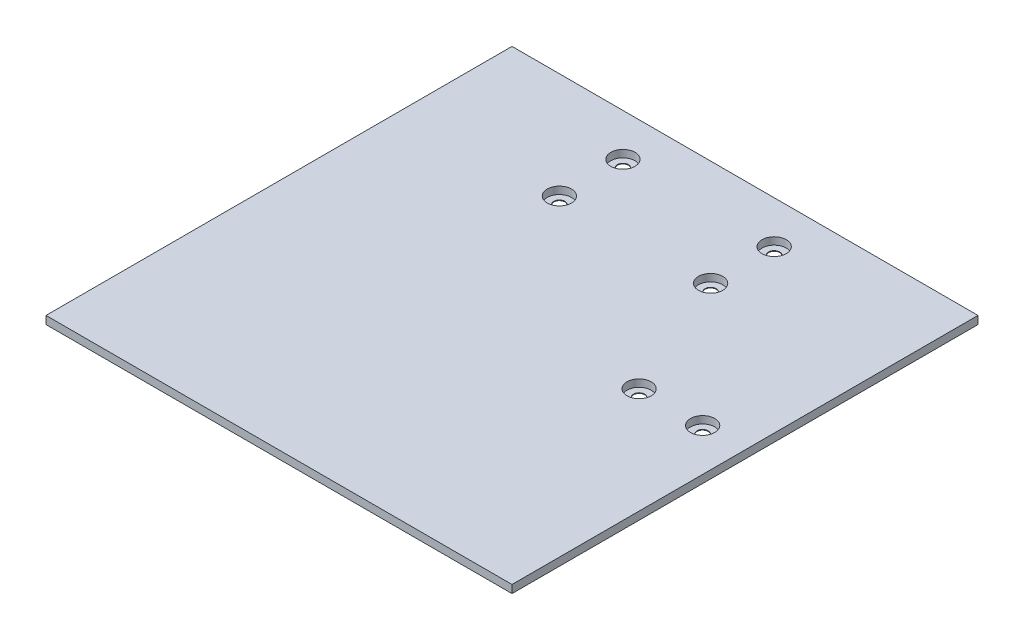
SolidWorks part; units mm, degrees
ref_plane "Front Plane" through (0, 0, 0) normal (0, 0, 1) x (1, 0, 0)
ref_plane "Top Plane" through (0, 0, 0) normal (0, 1, 0) x (1, 0, 0)
ref_plane "Right Plane" through (0, 0, 0) normal (1, 0, 0) x (0, 0, -1)
sketch "Sketch1" plane through (0, 0, 0) normal (0, 1, 0) x (1, 0, 0)
  line L0 (-264.036, 114.3) -> (114.3, 114.3) construction
  line L1 (-139.7, -139.7) -> (139.7, -139.7)
  line L2 (-139.7, -139.7) -> (-139.7, 139.7)
  line L3 (-139.7, 139.7) -> (139.7, 139.7)
  line L4 (139.7, -139.7) -> (139.7, 139.7)
  line L5 (-139.7, -139.7) -> (139.7, 139.7) construction
  line L6 (-139.7, 139.7) -> (139.7, -139.7) construction
  line L7 (-264.036, 76.2) -> (76.2, 76.2) construction
  line L8 (76.2, 76.2) -> (76.2, -273.3578) construction
  line L9 (114.3, 114.3) -> (114.3, -267.611) construction
  point P0 (0, 0)
  point P10 (184.7504, -181.3845)
  point P11 (250.6494, -267.611)
  point P13 (214.2533, -273.3578)
  dimension "D1" = 279.4
  dimension "D2" = 279.4
  dimension "D3" = 76.2
  dimension "D4" = 38.1
  dimension "D5" = 38.1
  dimension "D6" = 76.2
extrude "Boss-Extrude1" add sketch "Sketch1" along normal blind 4.7625 contours L1 L4 L3 L2
hole_wizard "CBORE for M6 Hex Head Bolt1" positions "Sketch6" profile "Sketch7" counterbore size "M6" standard "ANSI Metric" end condition through all
sketch "Sketch6" plane through (0, 4.7625, 0) normal (0, 1, 0) x (1, 0, 0)
  line L0 (-264.036, 76.2) -> (76.2, 76.2) construction
  line L2 (-264.036, 114.3) -> (114.3, 114.3) construction
  line L3 (76.2, 76.2) -> (76.2, -273.3578) construction
  line L4 (114.3, 114.3) -> (114.3, -267.611) construction
  point P0 (-47.7927, 76.2)
  point P6 (42.8821, 76.2)
  point P8 (-47.7927, 114.3)
  point P12 (42.8821, 114.3)
  point P14 (76.2, 0)
  point P18 (114.3, 0)
sketch "Sketch7" plane through (-47.7927, 4.7625, -76.2) normal (1, 0, 0) x (0, 0, 1)
  line L0 (0, 0) -> (0, 4.7625)
  line L1 (0, 4.7625) -> (3.3, 4.7625)
  line L3 (3.3, 4.7625) -> (3.3, 4.38)
  line L4 (3.3, 4.38) -> (7.275, 4.38)
  line L5 (7.275, 4.38) -> (7.275, 0)
  line L7 (7.275, 0) -> (0, 0)
  line L11 (0, -6.35) -> (0, 107.95) construction
  dimension "Thru Hole Dia." = 6.6
  dimension "Thru Hole Depth" = 4.7625
  dimension "C'Bore Dia." = 14.55
  dimension "C'Bore Depth" = 4.38
